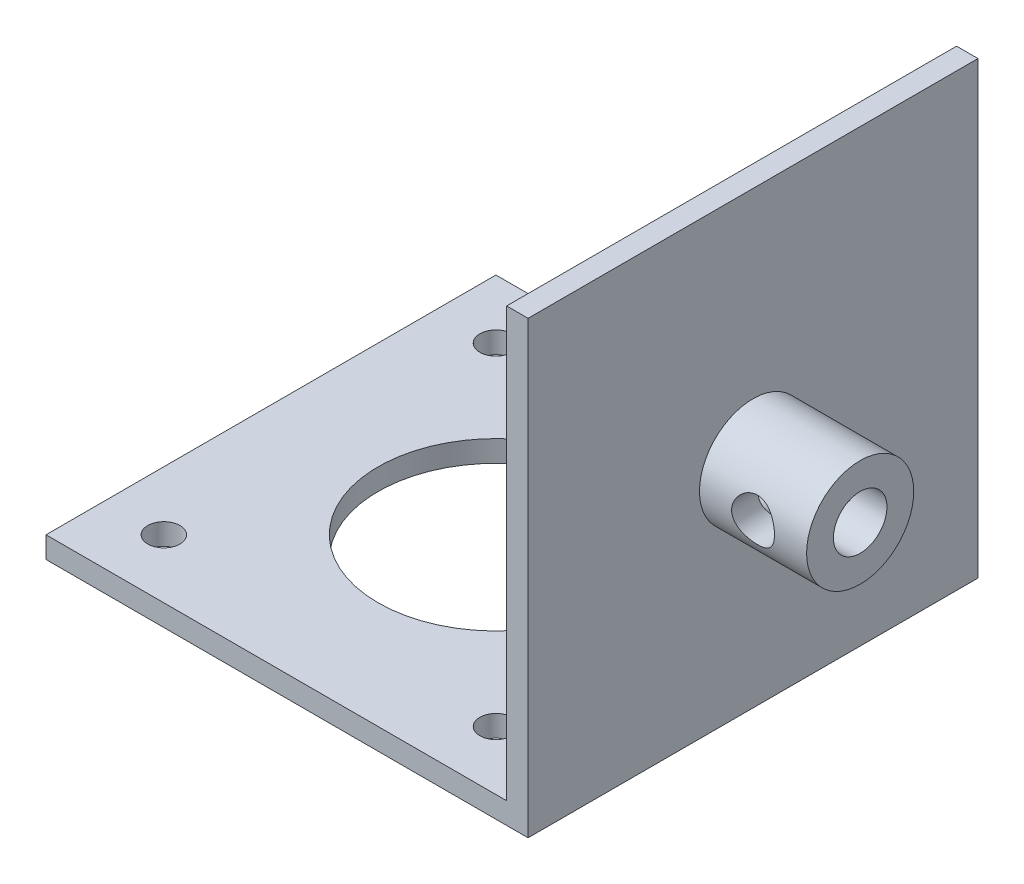
SolidWorks part; units mm, degrees
material "5052-H36"
ref_plane "前视基准面" through (0, 0, 0) normal (0, 0, 1) x (1, 0, 0)
ref_plane "上视基准面" through (0, 0, 0) normal (0, 1, 0) x (1, 0, 0)
ref_plane "右视基准面" through (0, 0, 0) normal (1, 0, 0) x (0, 0, -1)
sketch "草图1" plane through (0, 0, 0) normal (0, 1, 0) x (1, 0, 0)
  line L1 (0, 0) -> (45, 0)
  line L2 (0, 0) -> (0, 42)
  line L3 (0, 42) -> (45, 42)
  line L4 (45, 0) -> (45, 42)
extrude "凸台-拉伸1" add sketch "草图1" along normal blind 2
sketch "草图2" plane through (0, 2, 0) normal (0, 1, 0) x (1, 0, 0)
  line L0 (0, 0) -> (0, 21)
  line L1 (0, 42) -> (0, 0) construction
  circle A0 centre (21, 21) radius 11
  circle A1 centre (5.5, 5.5) radius 1.5
  circle A2 centre (5.5, 36.5) radius 1.5
  circle A3 centre (36.5, 36.5) radius 1.5
  circle A4 centre (36.5, 5.5) radius 1.5
extrude "切除-拉伸1" cut sketch "草图2" against normal blind 2 contours A2 | A0 | A1 | A4 | A3
sketch "草图3" plane through (0, 2, 0) normal (0, 1, 0) x (1, 0, 0)
  line L0 (45, 42) -> (43, 42)
  line L1 (45, 42) -> (0, 42) construction
  line L2 (43, 42) -> (43, 0)
  line L3 (0, 0) -> (45, 0) construction
  line L4 (43, 0) -> (45, 0)
  line L5 (45, 0) -> (45, 42)
extrude "凸台-拉伸2" add sketch "草图3" along normal blind 40
sketch "草图4" plane through (45, 0, 0) normal (1, 0, 0) x (0, 0, -1)
  line L0 (21, 0) -> (21, 20)
  line L1 (0, 0) -> (42, 0) construction
  circle A0 centre (21, 20) radius 5
  circle A1 centre (21, 20) radius 2.5
extrude "凸台-拉伸3" add sketch "草图4" along normal blind 10
sketch "草图5" plane through (0, 0, 0) normal (0, 0, 1) x (1, 0, 0)
  line L0 (45, 20) -> (50, 20)
  line L1 (45, 15) -> (45, 25) construction
  circle A0 centre (50, 20) radius 2
extrude "切除-拉伸2" cut sketch "草图5" against normal through all
